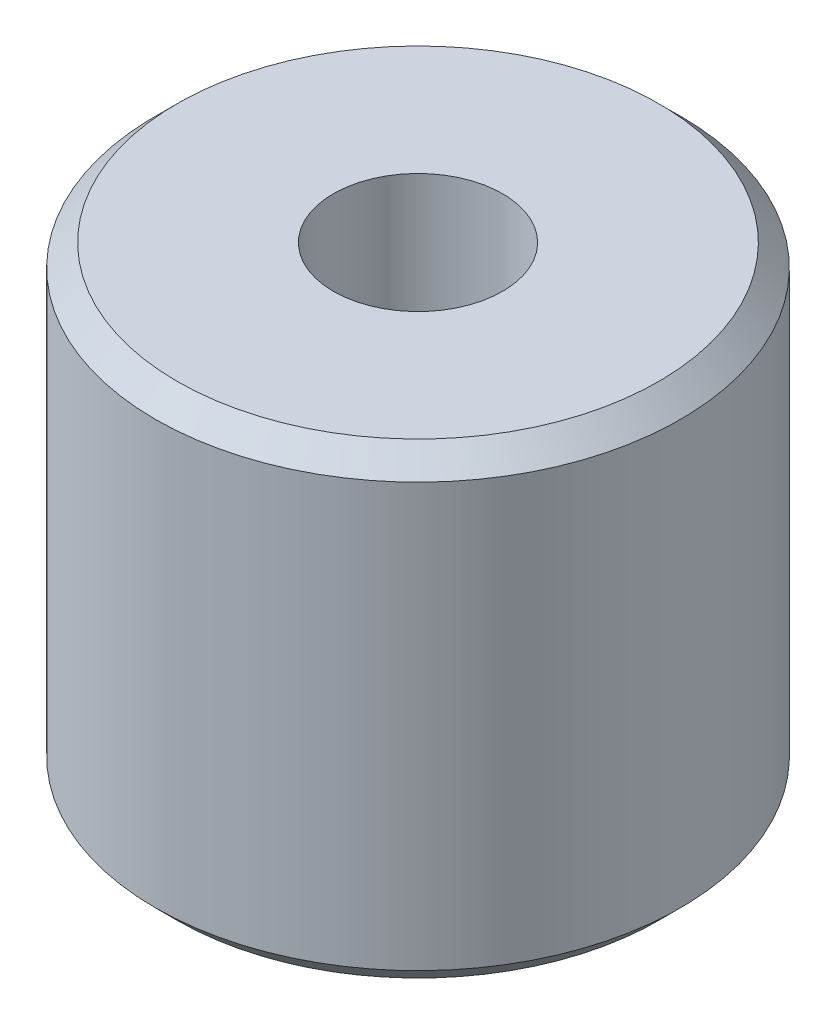
SolidWorks part; units mm, degrees
ref_plane "Front Plane" through (0, 0, 0) normal (0, 0, 1) x (1, 0, 0)
ref_plane "Top Plane" through (0, 0, 0) normal (0, 1, 0) x (1, 0, 0)
ref_plane "Right Plane" through (0, 0, 0) normal (1, 0, 0) x (0, 0, -1)
sketch "Sketch1" plane through (0, 0, 0) normal (0, 1, 0) x (1, 0, 0)
  circle A0 centre (0, 0) radius 18
  dimension "D1" = 36
extrude "Boss-Extrude1" add sketch "Sketch1" along normal blind 32
sketch "Sketch2" plane through (0, 32, 0) normal (0, 1, 0) x (1, 0, 0)
  circle A0 centre (0, 0) radius 5.8
  dimension "D1" = 11.6
extrude "Cut-Extrude1" cut sketch "Sketch2" against normal through all
chamfer "Chamfer1" distance 1.5 angle 45 2 edges at (0, 32, 18) (0, 0, 18)
